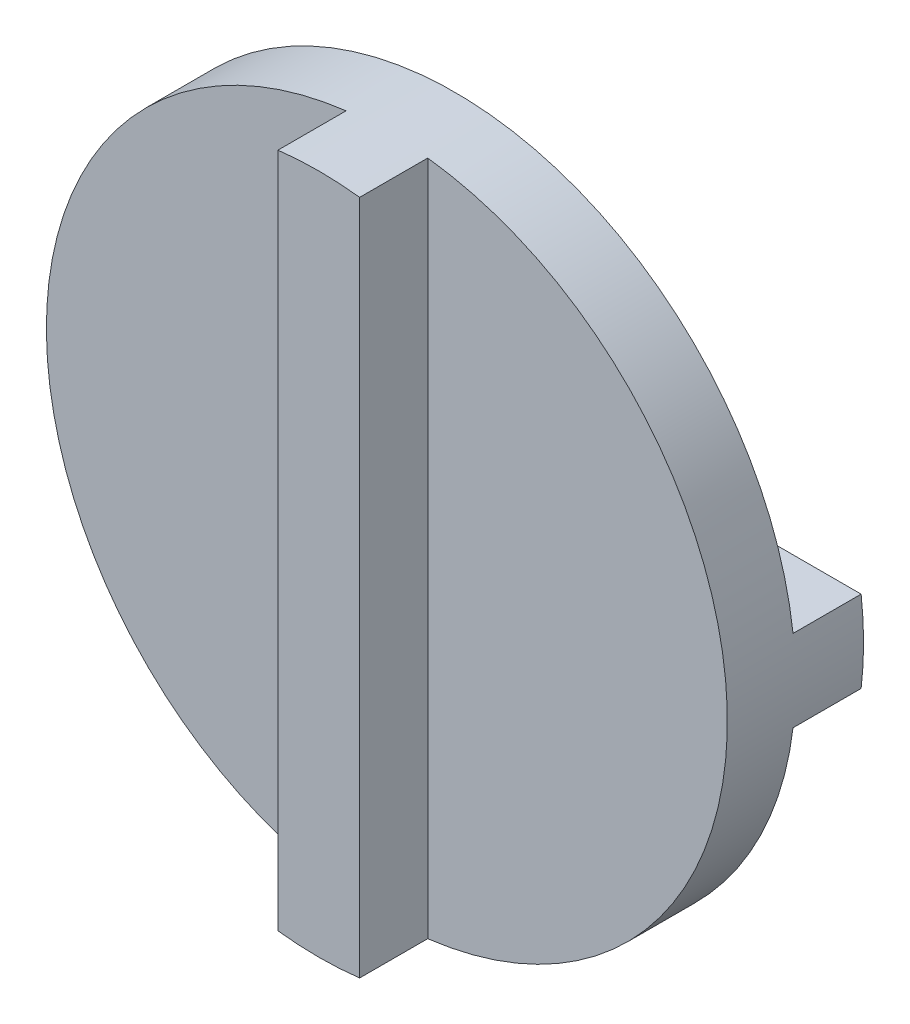
SolidWorks part; units mm, degrees
ref_plane "Front Plane" through (0, 0, 0) normal (0, 0, 1) x (1, 0, 0)
ref_plane "Top Plane" through (0, 0, 0) normal (0, 1, 0) x (1, 0, 0)
ref_plane "Right Plane" through (0, 0, 0) normal (1, 0, 0) x (0, 0, -1)
sketch "Sketch1" plane through (0, 0, 0) normal (0, 0, 1) x (1, 0, 0)
  circle A0 centre (0, 0) radius 50
  dimension "D1" = 100
extrude "Boss-Extrude1" add sketch "Sketch1" along normal blind 10
sketch "Sketch2" plane through (0, 0, 10) normal (0, 0, 1) x (1, 0, 0)
  line L2 (-6, 49.6387) -> (-6, -49.6387)
  line L4 (6, 49.6387) -> (6, -49.6387)
  circle A0 centre (0, 0) radius 50 construction
  arc A1 (-6, -49.6387) -> (6, -49.6387) centre (0, 0) ccw
  arc A2 (6, 49.6387) -> (-6, 49.6387) centre (0, 0) ccw
  dimension "D1" = 12
  dimension "D2" = 6
extrude "Boss-Extrude2" add sketch "Sketch2" along normal blind 10
sketch "Sketch3" plane through (0, 0, 0) normal (0, 0, -1) x (-1, 0, 0)
  line L1 (-49.6387, 6) -> (49.6387, 6)
  line L3 (-49.6387, -6) -> (49.6387, -6)
  circle A0 centre (0, 0) radius 50 construction
  arc A1 (-49.6387, 6) -> (-49.6387, -6) centre (0, 0) ccw
  arc A2 (49.6387, -6) -> (49.6387, 6) centre (0, 0) ccw
  dimension "D1" = 6
  dimension "D2" = 12
extrude "Boss-Extrude3" add sketch "Sketch3" along normal blind 10
